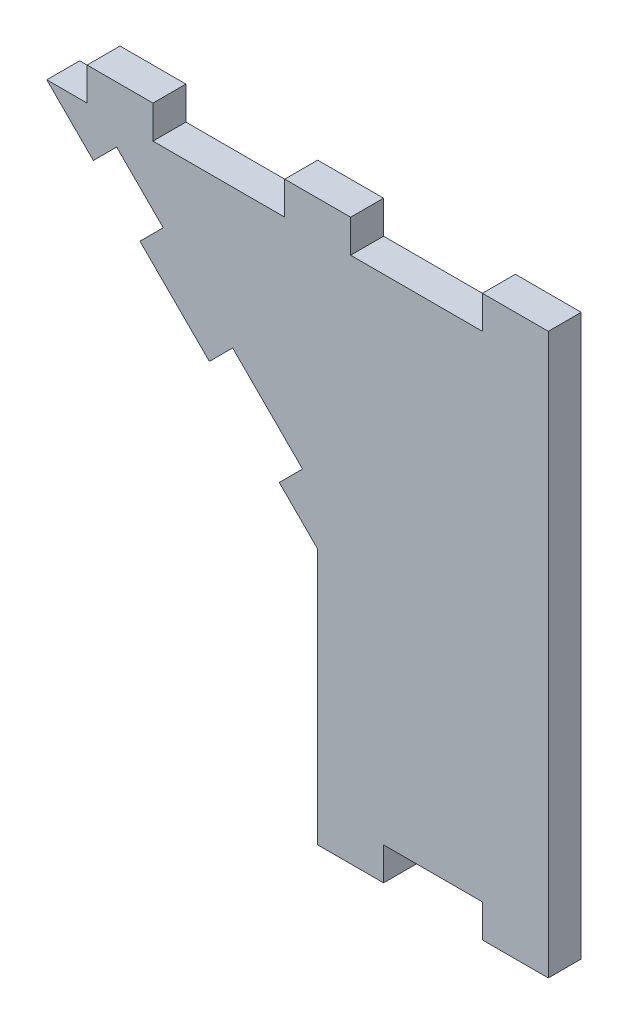
SolidWorks part; units mm, degrees
ref_plane "Plan de face" through (0, 0, 0) normal (0, 0, 1) x (1, 0, 0)
ref_plane "Plan de dessus" through (0, 0, 0) normal (0, 1, 0) x (1, 0, 0)
ref_plane "Plan de droite" through (0, 0, 0) normal (1, 0, 0) x (0, 0, -1)
sketch "Esquisse1" plane through (0, 0, 0) normal (0, 0, 1) x (1, 0, 0)
  line L0 (-35, 33.8817) -> (-40.8336, 39.7154)
  line L1 (-10, 0) -> (-25, 0)
  line L2 (0, 0) -> (0, 75)
  line L3 (-76.1183, 75) -> (-70, 75)
  line L4 (-35, 0) -> (-35, 33.8817)
  line L5 (-51.4402, 50.322) -> (-61.9761, 60.8579)
  line L6 (-69.0472, 67.9289) -> (-65.5117, 71.4645)
  line L7 (-61.9761, 60.8579) -> (-58.4406, 64.3934)
  line L8 (-65.5117, 71.4645) -> (-58.4406, 64.3934)
  line L9 (-60, 75) -> (-40, 75)
  line L10 (-51.4402, 50.322) -> (-47.9047, 53.8575)
  line L11 (-40.8336, 39.7154) -> (-37.2981, 43.2509)
  line L12 (-47.9047, 53.8575) -> (-37.2981, 43.2509)
  line L13 (-69.0472, 67.9289) -> (-76.1183, 75)
  line L14 (-30, 75) -> (-10, 75)
  line L15 (-35, 0) -> (-35, -5)
  line L16 (-35, -5) -> (-25, -5)
  line L17 (-25, 0) -> (-25, -5)
  line L18 (-70, 75) -> (-70, 80)
  line L19 (0, 0) -> (0, -5)
  line L20 (0, -5) -> (-10, -5)
  line L21 (-10, 0) -> (-10, -5)
  line L22 (-70, 80) -> (-60, 80)
  line L23 (-60, 75) -> (-60, 80)
  line L25 (0, 75) -> (0, 80)
  line L26 (0, 80) -> (-10, 80)
  line L27 (-10, 75) -> (-10, 80)
  line L29 (-40, 75) -> (-40, 80)
  line L30 (-40, 80) -> (-30, 80)
  line L31 (-30, 75) -> (-30, 80)
  dimension "D1" = 45
  dimension "D2" = 75
  dimension "D3" = 10
  dimension "D4" = 10
  dimension "D5" = 14.9
  dimension "D6" = 15
  dimension "D7" = 8.25
  dimension "D8" = 5
  dimension "D9" = 35
  dimension "D10" = 10
  dimension "D11" = 20
  dimension "D12" = 20
extrude "Boss.-Extru.1" add sketch "Esquisse1" along normal blind 5
